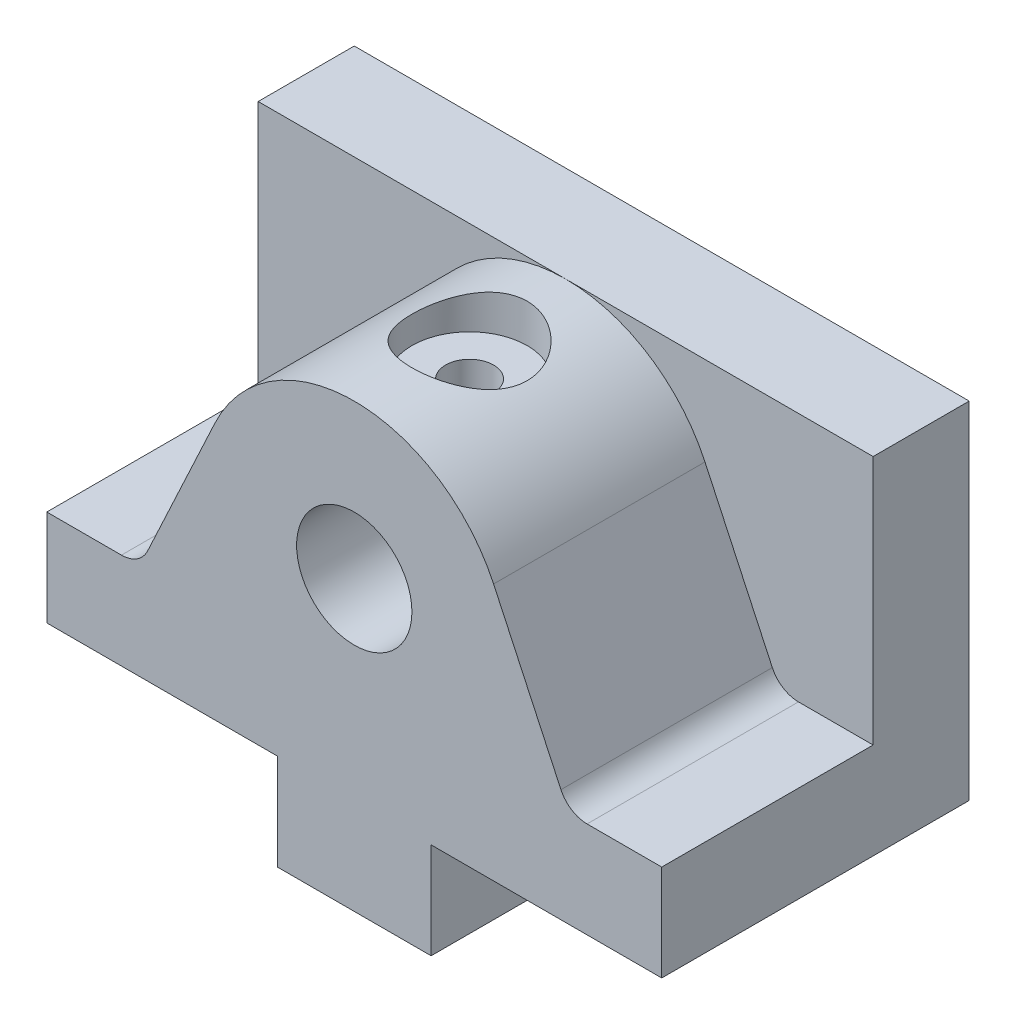
SolidWorks part; units mm, degrees
ref_plane "Front Plane" through (0, 0, 0) normal (0, 0, 1) x (1, 0, 0)
ref_plane "Top Plane" through (0, 0, 0) normal (0, 1, 0) x (1, 0, 0)
ref_plane "Right Plane" through (0, 0, 0) normal (1, 0, 0) x (0, 0, -1)
sketch "Sketch1" plane through (0, 0, 0) normal (0, 0, 1) x (1, 0, 0)
  line L0 (-8, 0) -> (8, 0)
  line L1 (-8, 0) -> (-8, 10)
  line L2 (-8, 10) -> (-32, 10)
  line L3 (0, 0) -> (0, 25.7049) construction
  line L4 (-32, 10) -> (-32, 20)
  line L5 (-32, 20) -> (-24.2283, 20)
  line L6 (8, 0) -> (8, 10)
  line L7 (8, 10) -> (32, 10)
  line L8 (32, 10) -> (32, 20)
  line L9 (32, 20) -> (24.2283, 20)
  line L10 (-14.5009, 36.7619) -> (-21.5094, 21.7321)
  line L11 (14.5009, 36.7619) -> (21.5094, 21.7321)
  circle A3 centre (0, 30) radius 6
  arc A4 (14.5009, 36.7619) -> (-14.5009, 36.7619) centre (0, 30) ccw
  arc A5 (21.5094, 21.7321) -> (24.2283, 20) centre (24.2283, 23) ccw
  arc A6 (-24.2283, 20) -> (-21.5094, 21.7321) centre (-24.2283, 23) ccw
  point P4 (0, 0)
  point P11 (0, 46)
  point P26 (22.3171, 20)
  point P29 (-22.3171, 20)
  dimension "D4" = 10
  dimension "D5" = 12
  dimension "D7" = 32
  dimension "D9" = 3
  dimension "D1" = 16
  dimension "D2" = 64
  dimension "D3" = 10
  dimension "D6" = 36
  dimension "D8" = 50
extrude "Boss-Extrude1" add sketch "Sketch1" against normal blind 22
sketch "Sketch2" plane through (0, 0, -22) normal (0, 0, -1) x (-1, 0, 0)
  line L0 (-32, 10) -> (-32, 20) construction
  line L1 (32, 20) -> (32, 10) construction
  line L2 (32, 10) -> (8, 10) construction
  line L3 (8, 10) -> (8, 0) construction
  line L4 (8, 0) -> (-8, 0) construction
  line L5 (-8, 0) -> (-8, 10) construction
  line L6 (-8, 10) -> (-32, 10) construction
  line L7 (-32, 10) -> (-32, 46)
  line L8 (32, 46) -> (32, 10)
  line L9 (32, 10) -> (8, 10)
  line L10 (8, 10) -> (8, 0)
  line L11 (8, 0) -> (-8, 0)
  line L12 (-8, 0) -> (-8, 10)
  line L13 (-8, 10) -> (-32, 10)
  line L14 (-32, 46) -> (32, 46)
  arc A0 (14.5009, 36.7619) -> (-14.5009, 36.7619) centre (0, 30) ccw construction
  circle A1 centre (0, 30) radius 6 construction
  circle A2 centre (0, 30) radius 6
  point P15 (0, 46)
extrude "Boss-Extrude2" add sketch "Sketch2" along normal blind 10
sketch "Sketch3" plane through (0, 0, -32) normal (0, 0, -1) x (-1, 0, 0)
  circle A0 centre (0, 30) radius 6
  circle A1 centre (0, 30) radius 6 construction
extrude "Boss-Extrude3" add sketch "Sketch3" against normal blind 8
hole_wizard "M6x1.0 Tapped Hole1" positions "Sketch4" profile "Sketch5" tap size "M6x1.0" standard "ANSI Metric"
sketch "Sketch4" plane through (0, 0, 0) normal (0, -1, 0) x (-1, 0, 0)
  point P0 (0, 8)
  point P2 (0, 24)
  dimension "D1" = 8
  dimension "D2" = 16
sketch "Sketch5" plane through (0, 0, -8) normal (1, 0, 0) x (0, 0, -1)
  line L0 (0, 0) -> (0, 17.4434)
  line L1 (0, 17.4434) -> (2.5, 16)
  line L2 (2.5, 16) -> (2.5, 0)
  line L5 (2.5, 0) -> (0, 0)
  line L10 (0, 17.4434) -> (-2.5, 16) construction
  line L11 (0, -6.35) -> (0, 107.95) construction
  dimension "Tap Drill Dia." = 5
  dimension "Tap Drill Depth" = 16
  dimension "Drill Angle" = 120
cosmetic thread "Hole Thread1" parameters "D1"=12, "D2"=6
cosmetic thread "Hole Thread2" parameters "D1"=12, "D2"=6
ref_plane "Plane1" through (0, 46, 0) normal (0, 1, 0) x (1, 0, 0)
ref_plane "Plane2" through (0, 42, 0) normal (0, 1, 0) x (1, 0, 0)
sketch "Sketch6" plane through (0, 42, 0) normal (0, 1, 0) x (1, 0, 0)
  line L1 (-32, 32) -> (32, 32) construction
  circle A0 centre (0, 12) radius 6
  dimension "D1" = 12
  dimension "D2" = 20
extrude "Cut-Extrude1" cut sketch "Sketch6" along normal blind 4
hole_wizard "M6x1.0 Tapped Hole2" positions "Sketch7" profile "Sketch9" tap size "M6x1.0" standard "ANSI Metric"
sketch "Sketch7" plane through (0, 42, 0) normal (0, 1, 0) x (1, 0, 0)
  point P0 (0, 12)
sketch "Sketch9" plane through (0, 42, -12) normal (1, 0, 0) x (0, 0, 1)
  line L0 (0, 0) -> (0, 6)
  line L1 (0, 6) -> (2.5, 6)
  line L2 (2.5, 6) -> (2.5, 0)
  line L5 (2.5, 0) -> (0, 0)
  line L11 (0, -6.35) -> (0, 107.95) construction
  dimension "Thru Tap Drill Dia." = 5
  dimension "Thru Tap Drill Depth" = 6
cosmetic thread "Hole Thread3" parameters "D2"=6
